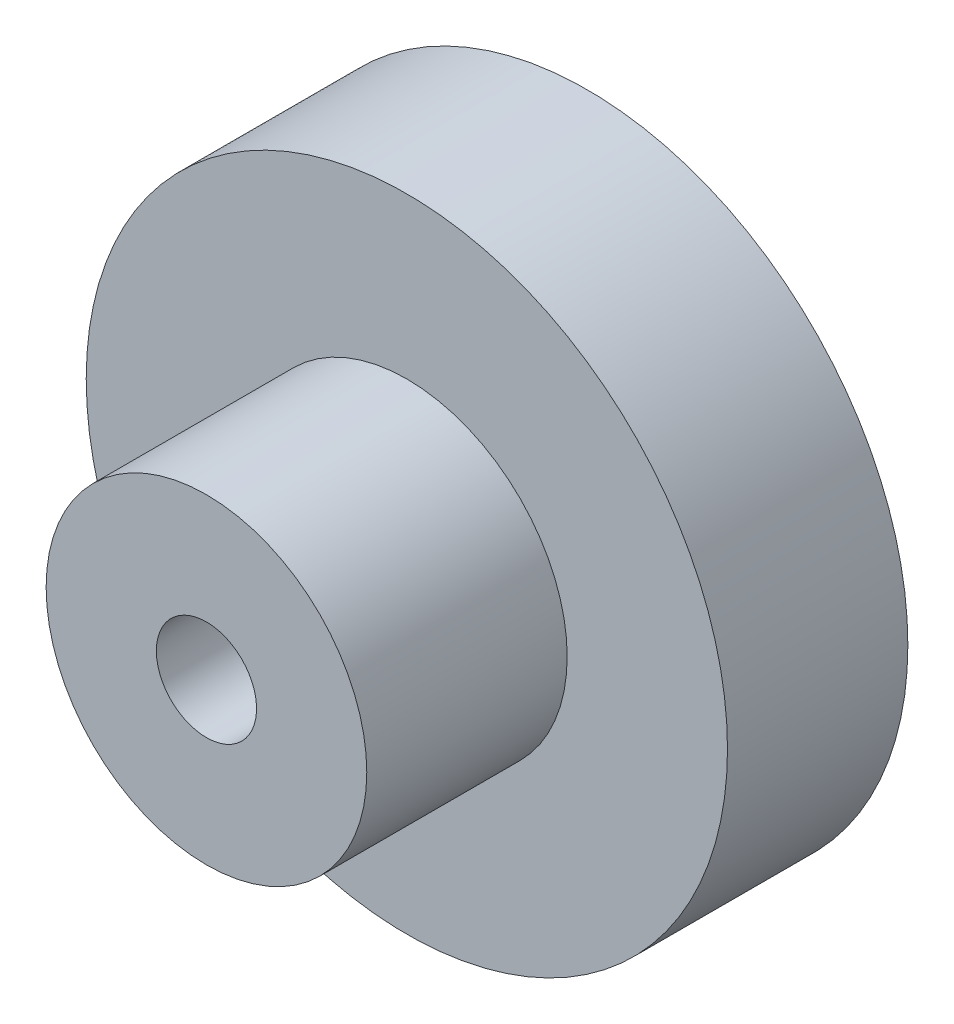
SolidWorks part; units mm, degrees
material "AISI Type 316L stainless steel"
ref_plane "Top Plane" through (0, 0, 0) normal (0, 0, 1) x (1, 0, 0)
ref_plane "Front Plane" through (0, 0, 0) normal (0, 1, 0) x (1, 0, 0)
ref_plane "Right Plane" through (0, 0, 0) normal (1, 0, 0) x (0, 0, -1)
sketch "Sketch1" plane through (0, 0, 0) normal (1, 0, 0) x (0, 0, -1)
  line L0 (-7.5205, 4) -> (-2.5205, 4)
  line L1 (-2.5205, 4) -> (-2.5205, 8)
  line L2 (-2.5205, 8) -> (1.9795, 8)
  line L3 (1.9795, 8) -> (1.9795, 1.25)
  line L4 (1.9795, 1.25) -> (-7.5205, 1.25)
  line L5 (-7.5205, 1.25) -> (-7.5205, 4)
  line L6 (0, 0) -> (-12.8413, 0) construction
  dimension "D1" = 8
  dimension "D2" = 4
  dimension "D3" = 5
  dimension "D4" = 9.5
  dimension "D5" = 1.25
revolve "Revolve1" add sketch "Sketch1" angle 360 about L6
